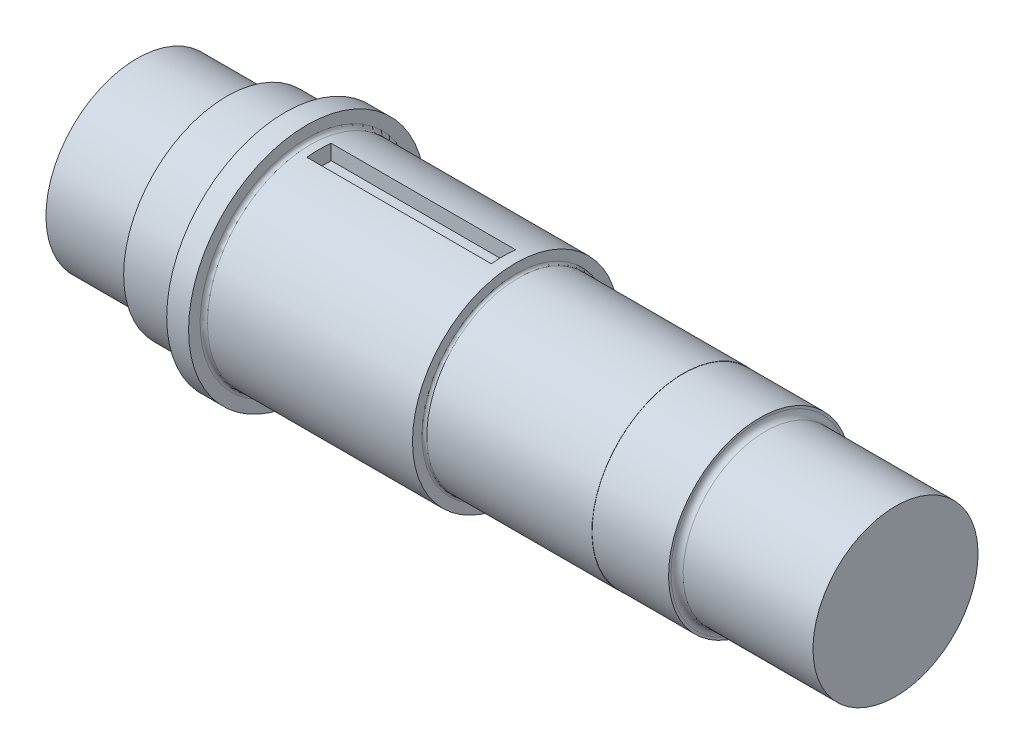
SolidWorks part; units mm, degrees
ref_plane "Front Plane" through (0, 0, 0) normal (0, 0, 1) x (1, 0, 0)
ref_plane "Top Plane" through (0, 0, 0) normal (0, 1, 0) x (1, 0, 0)
ref_plane "Right Plane" through (0, 0, 0) normal (1, 0, 0) x (0, 0, -1)
sketch "Sketch1" plane through (0, 0, 0) normal (0, 0, 1) x (1, 0, 0)
  line L0 (-289.1479, -40.9475) -> (335.8521, -40.9475)
  line L1 (-289.1479, -40.9475) -> (-289.1479, 34.0525)
  line L2 (-289.1479, 34.0525) -> (-215.1479, 34.0525)
  line L3 (-215.1479, 44.0525) -> (-215.1479, 34.0525)
  line L4 (-215.1479, 44.0525) -> (-167.1479, 44.0525)
  line L5 (-167.1479, 56.5525) -> (-167.1479, 44.0525)
  line L6 (-167.1479, 56.5525) -> (-149.1479, 56.5525)
  line L7 (-149.1479, 56.5525) -> (-149.1479, 44.0525)
  line L8 (-149.1479, 44.0525) -> (22.8521, 44.0525)
  line L9 (22.8521, 44.0525) -> (22.8521, 34.2525)
  line L11 (22.8521, 34.2525) -> (160.8521, 34.2525)
  line L12 (160.8521, 34.0525) -> (160.8521, 34.2525)
  line L14 (160.8521, 34.0525) -> (223.8521, 34.0525)
  line L15 (223.8521, 27.0525) -> (223.8521, 34.0525)
  line L17 (223.8521, 27.0525) -> (335.8521, 27.0525)
  line L18 (335.8521, 27.0525) -> (335.8521, -40.9475)
  dimension "D1" = 75
  dimension "D2" = 74
  dimension "D4" = 48
  dimension "D6" = 18
  dimension "D7" = 172
  dimension "D9" = 138
  dimension "D11" = 63
  dimension "D13" = 112
revolve "Revolve1" add sketch "Sketch1" angle 360 about L0
fillet "Fillet1" radius 3 1 edges at (-149.1479, -125.9475, 0)
fillet "Fillet2" radius 2 1 edges at (22.8521, -116.1475, 0)
fillet "Fillet3" radius 5 1 edges at (223.8521, -108.9475, 0)
sketch "Sketch2" plane through (0, 0, 0) normal (0, 0, 1) x (1, 0, 0)
  line L2 (-139.1479, 44.0525) -> (12.8521, 44.0525)
  line L3 (22.8521, 44.0525) -> (-146.1479, 44.0525) construction
  line L6 (-139.1479, 44.0525) -> (-139.1479, 31.0525)
  line L7 (-139.1479, 31.0525) -> (12.8521, 31.0525)
  line L8 (12.8521, 44.0525) -> (12.8521, 31.0525)
  dimension "D2" = 152
  dimension "D3" = 13
extrude "Cut-Extrude2" cut sketch "Sketch2" against normal mid plane 20
